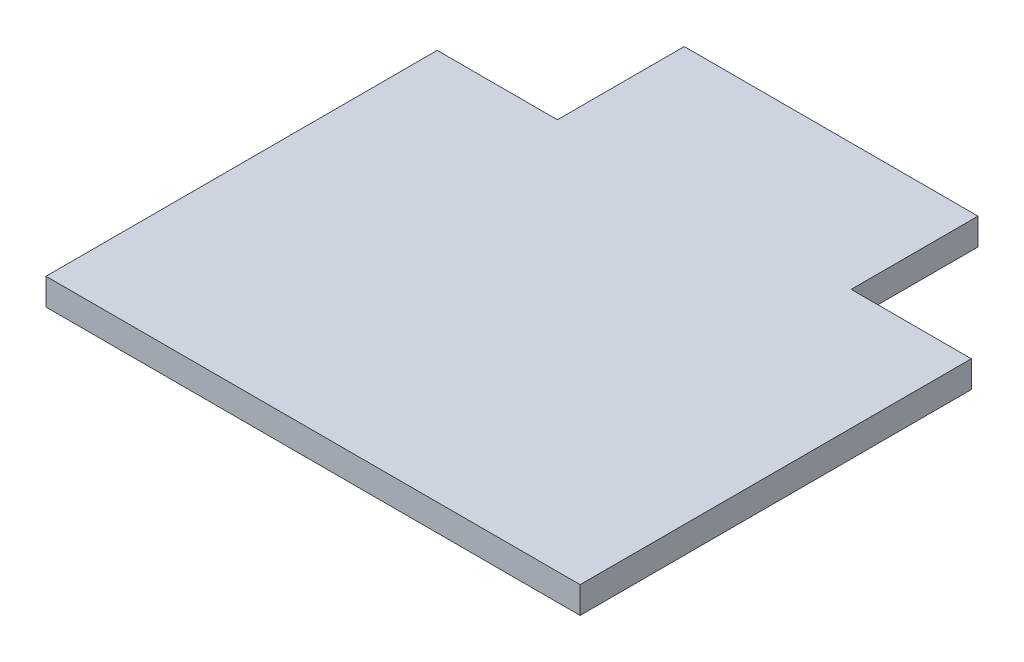
SolidWorks part; units mm, degrees
ref_plane "前视基准面" through (0, 0, 0) normal (0, 0, 1) x (1, 0, 0)
ref_plane "上视基准面" through (0, 0, 0) normal (0, 1, 0) x (1, 0, 0)
ref_plane "右视基准面" through (0, 0, 0) normal (1, 0, 0) x (0, 0, -1)
other "Configuration Table"
sketch "草图1" plane through (0, 0, 0) normal (0, 1, 0) x (1, 0, 0)
  line L0 (0, 0) -> (0, -29.3)
  line L1 (0, -29.3) -> (40, -29.3)
  line L2 (40, -29.3) -> (40, 0)
  line L3 (40, 0) -> (31, 0)
  line L4 (31, 0) -> (31, 9.5)
  line L5 (31, 9.5) -> (9, 9.5)
  line L6 (9, 9.5) -> (9, 0)
  line L7 (9, 0) -> (0, 0)
  point P8 (28.0347, 0)
  point P10 (28.0347, 0)
  point P11 (31.7194, 0)
  point P12 (30.6448, 0)
  point P13 (12.9903, 10.1819)
  dimension "D1" = 40
  dimension "D2" = 29.3
  dimension "D3" = 9.5
  dimension "D4" = 22
  dimension "D5" = 9
extrude "凸台-拉伸1" add sketch "草图1" along normal blind 2
